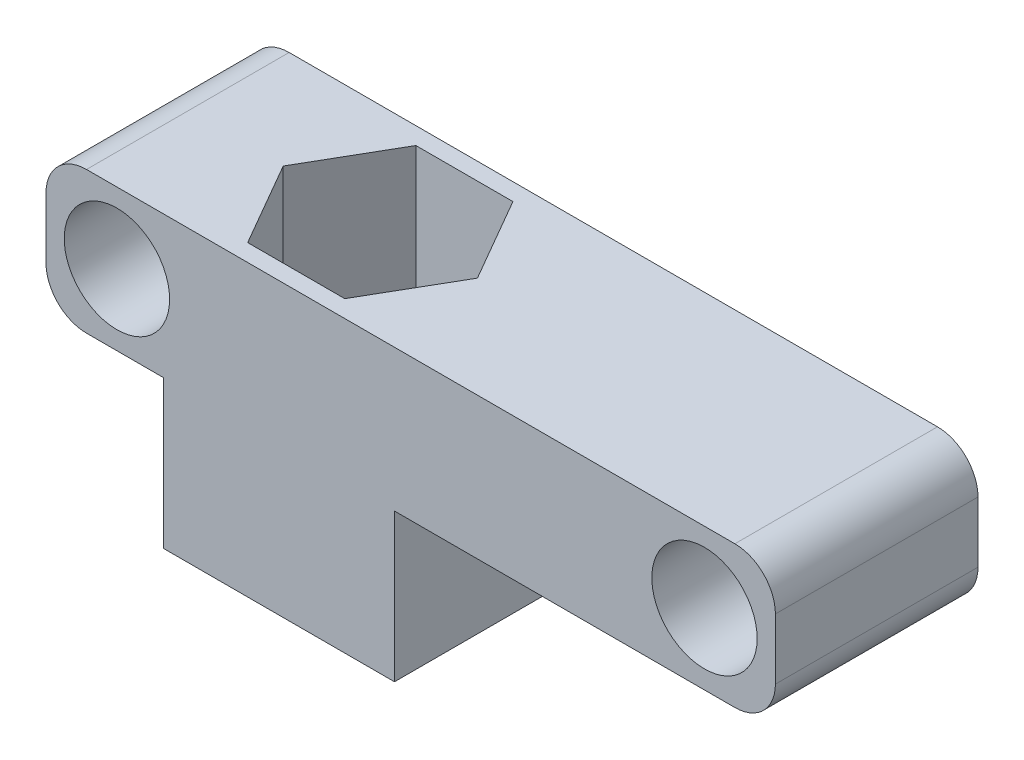
SolidWorks part; units mm, degrees
ref_plane "Alzado" through (0, 0, 0) normal (0, 0, 1) x (1, 0, 0)
ref_plane "Planta" through (0, 0, 0) normal (0, 1, 0) x (1, 0, 0)
ref_plane "Vista lateral" through (0, 0, 0) normal (1, 0, 0) x (0, 0, -1)
sketch "Croquis1" plane through (0, 0, 0) normal (0, 0, 1) x (1, 0, 0)
  line L1 (-46.0167, 15.878) -> (-10.0167, 15.878)
  line L2 (-46.0167, 15.878) -> (-46.0167, 8.878)
  line L3 (-46.0167, 8.878) -> (-10.0167, 8.878)
  line L4 (-10.0167, 15.878) -> (-10.0167, 8.878)
  circle A0 centre (-42.5167, 12.378) radius 2.6
  circle A1 centre (-13.5167, 12.378) radius 2.6
  dimension "D5" = 2
  dimension "D1" = 36
  dimension "D2" = 7
  dimension "D3" = 3.5
  dimension "D4" = 3.5
extrude "Saliente-Extruir1" add sketch "Croquis1" along normal blind 10
sketch "Croquis2" plane through (0, 8.878, 0) normal (0, -1, 0) x (1, 0, 0)
  line L0 (-46.0167, 10) -> (-10.0167, 10) construction
  line L1 (-46.0167, 10) -> (-46.0167, 0) construction
  line L3 (-29.7247, 5) -> (-32.1207, 9.15)
  line L4 (-32.1207, 9.15) -> (-36.9127, 9.15)
  line L5 (-36.9127, 9.15) -> (-39.3087, 5)
  line L6 (-39.3087, 5) -> (-36.9127, 0.85)
  line L7 (-36.9127, 0.85) -> (-32.1207, 0.85)
  line L8 (-32.1207, 0.85) -> (-29.7247, 5)
  circle A1 centre (-34.5167, 5) radius 4.15 construction
  dimension "D1" = 5
  dimension "D3" = 8.3
  dimension "D2" = 11.5
extrude "Cortar-Extruir1" cut sketch "Croquis2" against normal up to vertex (7 mm away)
sketch "Croquis4" plane through (0, 8.878, 0) normal (0, -1, 0) x (1, 0, 0)
  line L0 (-39.2167, 5) -> (-40.2167, 5) construction
  line L1 (-29.8167, 5) -> (-32.1667, 9.0703)
  line L2 (-32.1667, 9.0703) -> (-36.8667, 9.0703)
  line L3 (-36.8667, 9.0703) -> (-39.2167, 5)
  line L4 (-39.2167, 5) -> (-36.8667, 0.9297)
  line L5 (-36.8667, 0.9297) -> (-32.1667, 0.9297)
  line L6 (-32.1667, 0.9297) -> (-29.8167, 5)
  line L7 (-46.0167, 10) -> (-10.0167, 10) construction
  line L8 (-40.2167, 10) -> (-28.8167, 10)
  line L9 (-40.2167, 10) -> (-40.2167, 0)
  line L10 (-40.2167, 0) -> (-28.8167, 0)
  line L11 (-28.8167, 10) -> (-28.8167, 0)
  line L12 (-46.0167, 0) -> (-10.0167, 0) construction
  circle A1 centre (-34.5167, 5) radius 4.0703 construction
  dimension "D1" = 11.4
extrude "Saliente-Extruir2" add sketch "Croquis4" along normal blind 5
fillet "Redondeo1" radius 2 4 edges at (-10.0167, 15.878, 5) (-10.0167, 8.878, 5) (-46.0167, 8.878, 5) (-46.0167, 15.878, 5)
sketch "Croquis5" plane through (0, 3.878, 0) normal (0, -1, 0) x (1, 0, 0)
  line L0 (-40.2167, 0) -> (-28.8167, 10) construction
  line L1 (-40.2167, 10) -> (-28.8167, 10)
  line L2 (-40.2167, 10) -> (-40.2167, 0)
  line L3 (-40.2167, 0) -> (-28.8167, 0)
  line L4 (-28.8167, 10) -> (-28.8167, 0)
  circle A0 centre (-34.5167, 5) radius 3.25
extrude "Saliente-Extruir3" add sketch "Croquis5" along normal blind 2.3
